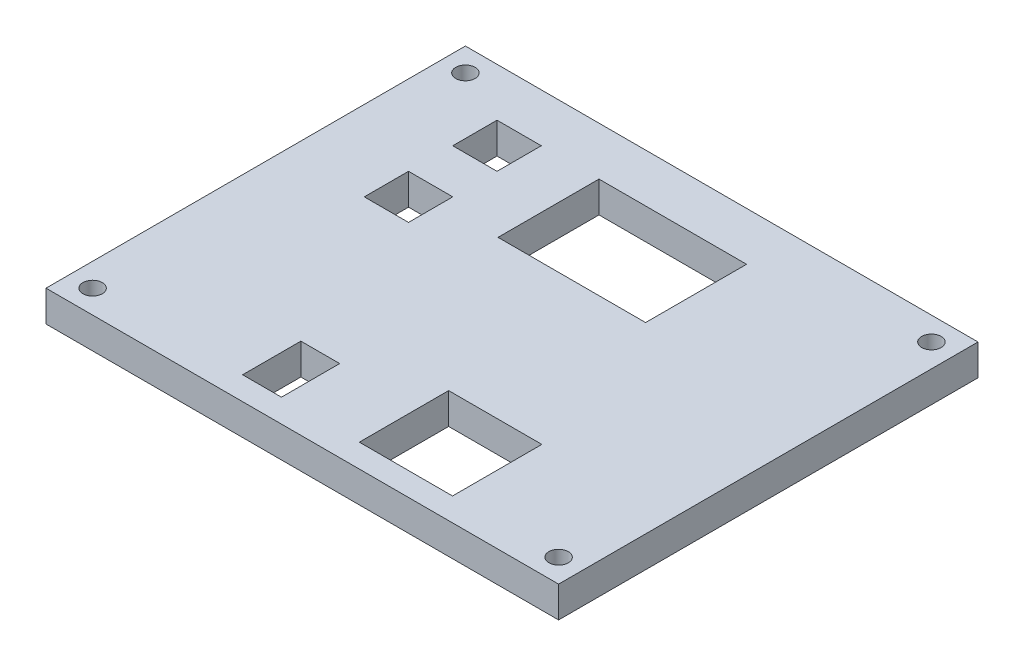
SolidWorks part; units mm, degrees
ref_plane "前视基准面" through (0, 0, 0) normal (0, 0, 1) x (1, 0, 0)
ref_plane "上视基准面" through (0, 0, 0) normal (0, 1, 0) x (1, 0, 0)
ref_plane "右视基准面" through (0, 0, 0) normal (1, 0, 0) x (0, 0, -1)
sketch "草图2" plane through (0, 0, 0) normal (0, 1, 0) x (1, 0, 0)
  line L1 (0, 0) -> (66, 0)
  line L2 (0, 0) -> (0, -54)
  line L3 (0, -54) -> (66, -54)
  line L4 (66, 0) -> (66, -54)
  dimension "D1" = 66
  dimension "D2" = 54
extrude "凸台-拉伸1" add sketch "草图2" along normal blind 4 contours L1 L4 L3 L2
sketch "草图3" plane through (0, 4, 0) normal (0, 1, 0) x (1, 0, 0)
  line L0 (33, 0) -> (33, -54) construction
  line L1 (0, 0) -> (66, 0) construction
  line L2 (0, -54) -> (66, -54) construction
  line L3 (0, -27) -> (66, -27) construction
  line L4 (0, 0) -> (0, -54) construction
  line L5 (66, 0) -> (66, -54) construction
  point P12 (3, -3)
  point P13 (3, -51)
  point P14 (63, -51)
  point P15 (63, -3)
  dimension "D1" = 3
  dimension "D2" = 3
hole_wizard "M3 螺纹孔1" positions "草图4" profile "草图5" tap size "M3" standard "GB" end condition up to next
sketch "草图4" plane through (0, 4, 0) normal (0, 1, 0) x (1, 0, 0)
  point P0 (3, -3)
  point P3 (3, -51)
  point P6 (63, -51)
  point P9 (63, -3)
sketch "草图5" plane through (3, 4, 3) normal (1, 0, 0) x (0, 0, 1)
  line L0 (0, 0) -> (0, 4)
  line L1 (0, 4) -> (1.25, 4)
  line L2 (1.25, 4) -> (1.25, 0)
  line L5 (1.25, 0) -> (0, 0)
  line L11 (0, -6.35) -> (0, 107.95) construction
  dimension "通孔螺纹孔钻头直径" = 2.5
  dimension "通孔螺纹孔钻头深度" = 4
cosmetic thread "孔螺蚊线1" parameters "D2"=3
cosmetic thread "孔螺蚊线2" parameters "D2"=3
cosmetic thread "孔螺蚊线3" parameters "D2"=3
cosmetic thread "孔螺蚊线4" parameters "D2"=3
sketch "草图7" plane through (0, 4, 0) normal (0, 1, 0) x (1, 0, 0)
  line L0 (10.3296, -51) -> (32.2096, -51) construction
  line L1 (22.3151, -43.5) -> (27.3151, -43.5)
  line L2 (22.3151, -43.5) -> (22.3151, -51)
  line L3 (22.3151, -51) -> (27.3151, -51)
  line L4 (27.3151, -43.5) -> (27.3151, -51)
  line L5 (10.3072, -6.2346) -> (16.0072, -6.2346)
  line L6 (10.3072, -6.2346) -> (10.3072, -11.9346)
  line L7 (10.3072, -11.9346) -> (16.0072, -11.9346)
  line L8 (16.0072, -6.2346) -> (16.0072, -11.9346)
  line L9 (10.3072, -17.6307) -> (16.0072, -17.6307)
  line L10 (23.436, -6.2346) -> (42.436, -6.2346)
  line L11 (23.436, -6.2346) -> (23.436, -19.2346)
  line L12 (23.436, -19.2346) -> (42.436, -19.2346)
  line L13 (42.436, -6.2346) -> (42.436, -19.2346)
  line L14 (10.3072, -17.6307) -> (10.3072, -23.3307)
  line L15 (37.3428, -39.5) -> (49.3428, -39.5)
  line L16 (37.3428, -39.5) -> (37.3428, -51)
  line L17 (37.3428, -51) -> (49.3428, -51)
  line L18 (49.3428, -39.5) -> (49.3428, -51)
  line L19 (10.3072, -23.3307) -> (16.0072, -23.3307)
  line L20 (16.0072, -17.6307) -> (16.0072, -23.3307)
  point P4 (23.436, -6.2346)
  dimension "D1" = 7.5
  dimension "D2" = 5
  dimension "D3" = 5.7
  dimension "D4" = 5.7
  dimension "D5" = 19
  dimension "D6" = 13
  dimension "D9" = 12
  dimension "D10" = 11.5
extrude "切除-拉伸1" cut sketch "草图7" against normal blind 4
